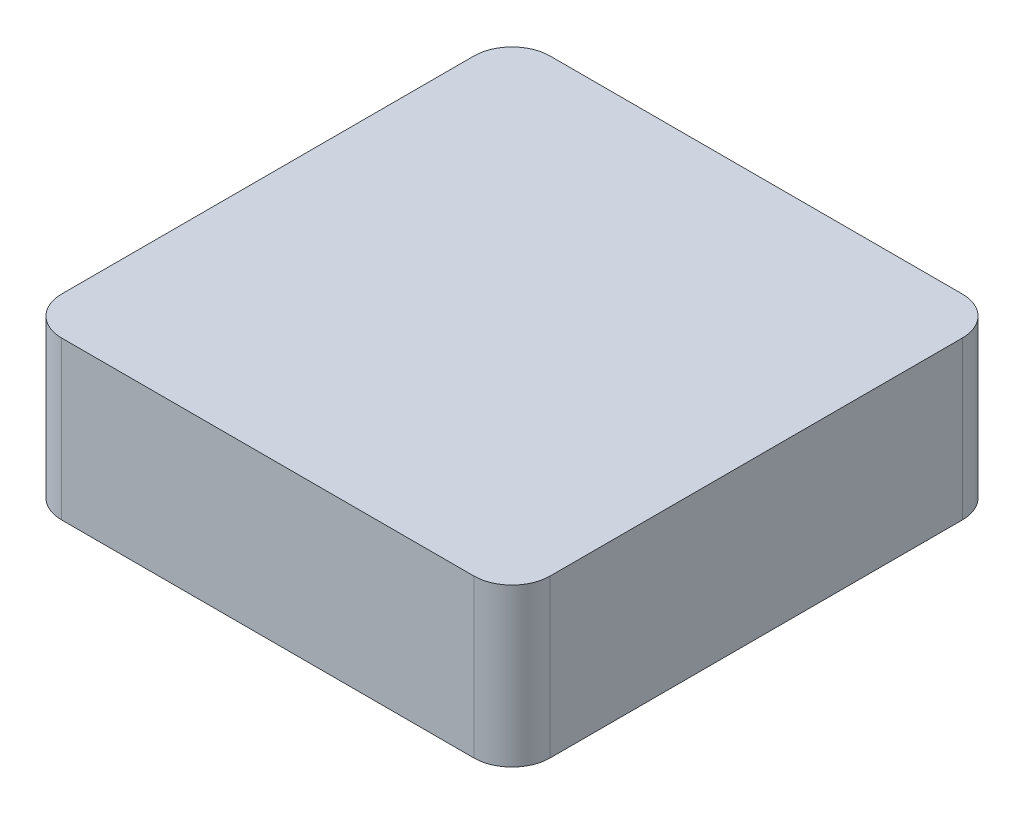
SolidWorks part; units mm, degrees
ref_plane "正面" through (0, 0, 0) normal (0, 0, 1) x (1, 0, 0)
ref_plane "平面" through (0, 0, 0) normal (0, 1, 0) x (1, 0, 0)
ref_plane "右側面" through (0, 0, 0) normal (1, 0, 0) x (0, 0, -1)
sketch "ｽｹｯﾁ1" plane through (0, 0, 0) normal (0, 1, 0) x (1, 0, 0)
  line L1 (-64, -64) -> (64, -64)
  line L2 (-64, -64) -> (-64, 64)
  line L3 (-64, 64) -> (64, 64)
  line L4 (64, -64) -> (64, 64)
  line L5 (-64, -64) -> (64, 64) construction
  line L6 (-64, 64) -> (64, -64) construction
  point P0 (0, 0)
  dimension "D1" = 128
extrude "ﾎﾞｽ - 押し出し1" add sketch "ｽｹｯﾁ1" along normal mid plane 41.3
fillet "ﾌｨﾚｯﾄ1" radius 10 4 edges at (64, 0, 64) (-64, 0, -64) (64, 0, -64) (-64, 0, 64)
